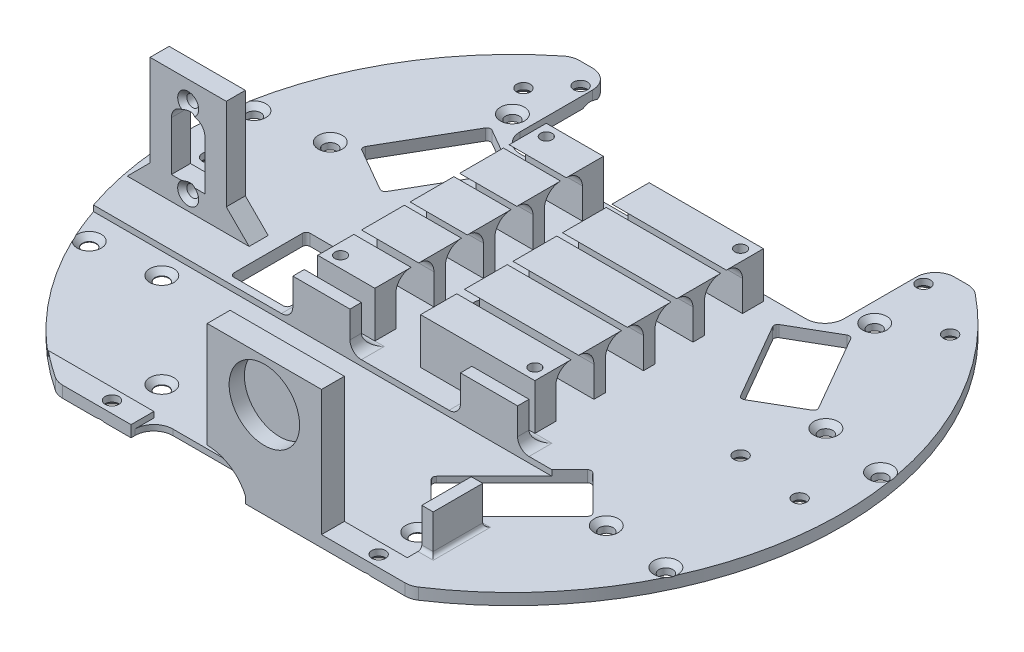
SolidWorks part; units mm, degrees
other "Camera1"
material "PET"
ref_plane "Front Plane" through (0, 0, 0) normal (0, 0, 1) x (1, 0, 0)
ref_plane "Top Plane" through (0, 0, 0) normal (0, 1, 0) x (1, 0, 0)
ref_plane "Right Plane" through (0, 0, 0) normal (1, 0, 0) x (0, 0, -1)
sketch "Sketch1" plane through (0, 0, 0) normal (0, 1, 0) x (1, 0, 0)
  line L0 (-52.6579, 68.6251) -> (52.6579, 68.6251)
  line L1 (52.6579, 68.6251) -> (0, 0) construction
  line L2 (0, 0) -> (-52.6579, 68.6251) construction
  line L3 (0, -100.6233) -> (0, 107.1722) construction
  line L4 (110.1779, 0) -> (-109.5879, 0) construction
  line L5 (0, 0) -> (40.7032, 23.5) construction
  line L6 (34.4532, 34.3253) -> (46.9532, 12.6747)
  line L7 (46.9532, 12.6747) -> (59.9436, 20.1747)
  line L8 (59.9436, 20.1747) -> (47.4436, 41.8253)
  line L9 (47.4436, 41.8253) -> (34.4532, 34.3253)
  line L10 (0, 0) -> (33.234, -33.234) construction
  line L11 (43.8406, -22.6274) -> (22.6274, -43.8406)
  line L12 (22.6274, -43.8406) -> (33.234, -54.4472)
  line L13 (33.234, -54.4472) -> (54.4472, -33.234)
  line L14 (54.4472, -33.234) -> (43.8406, -22.6274)
  line L15 (0, 0) -> (-33.234, -33.234) construction
  line L16 (-22.6274, -43.8406) -> (-33.234, -54.4472) construction
  line L17 (-33.234, -54.4472) -> (-54.4472, -33.234) construction
  line L18 (-54.4472, -33.234) -> (-43.8406, -22.6274) construction
  line L19 (-43.8406, -22.6274) -> (-22.6274, -43.8406) construction
  line L20 (-47.4436, 41.8253) -> (-34.4532, 34.3253)
  line L21 (-59.9436, 20.1747) -> (-47.4436, 41.8253)
  line L22 (-46.9532, 12.6747) -> (-59.9436, 20.1747)
  line L23 (-34.4532, 34.3253) -> (-46.9532, 12.6747)
  line L24 (0, 0) -> (-40.7032, 23.5) construction
  arc A0 (-52.6579, 68.6251) -> (52.6579, 68.6251) centre (0, 0) ccw
  arc A1 (52.6579, 68.6251) -> (-52.6579, 68.6251) centre (0, 0) ccw construction
  point P11 (40.7032, 23.5)
  point P18 (33.234, -33.234)
  dimension "D1" = 173
  dimension "D2" = 75
  dimension "D3" = 60
  dimension "D4" = 45
  dimension "D5" = 62
  dimension "D6" = 15
  dimension "D7" = 25
  dimension "D8" = 30
extrude "Boss-Extrude1" add sketch "Sketch1" along normal blind 3
hole_wizard "CSK for M3 Countersunk Flat Head Screw8" positions "Sketch42" profile "Sketch43" countersink size "M3" standard "DIN" end condition through all
sketch "Sketch42" plane through (0, 3, 0) normal (0, 1, 0) x (1, 0, 0)
  line L0 (0, 0) -> (56.2917, 32.5) construction
  line L2 (0, 0) -> (45.9619, -45.9619) construction
  line L4 (0, -101.1131) -> (0, 85.3109) construction
  line L6 (100.6982, 0) -> (-96.3433, 0) construction
  line L9 (58.3363, -33.5876) -> (33.5876, -58.3363) construction
  line L11 (65.0417, 17.3446) -> (47.5417, 47.6554) construction
  line L12 (0, 0) -> (-56.2917, 32.5) construction
  line L13 (-65.0417, 17.3446) -> (-47.5417, 47.6554) construction
  line L14 (-58.3363, -33.5876) -> (-33.5876, -58.3363) construction
  line L15 (0, 0) -> (-45.9619, -45.9619) construction
  line L16 (0, 0) -> (-75.6767, -35.2886) construction
  line L18 (-82.2314, 14.4996) -> (0, 0) construction
  arc A4 (-75.6767, -35.2886) -> (-82.2314, 14.4996) centre (0, 0) cw construction
  point P20 (58.3363, -33.5876)
  point P21 (33.5876, -58.3363)
  point P24 (65.0417, 17.3446)
  point P25 (47.5417, 47.6554)
  point P28 (56.2917, 32.5)
  point P29 (45.9619, -45.9619)
  point P42 (-47.5417, 47.6554)
  point P43 (-65.0417, 17.3446)
  point P44 (-33.5876, -58.3363)
  point P45 (-58.3363, -33.5876)
  point P51 (-75.6767, -35.2886)
  point P85 (-82.2314, 14.4996)
  point P103 (75.6767, -35.2886)
  point P104 (82.2314, 14.4996)
  dimension "D6" = 25
  dimension "D4" = 83.5
  dimension "D1" = 45
  dimension "D2" = 60
  dimension "D3" = 35
  dimension "D5" = 65
  dimension "5" = 35
sketch "Sketch43" plane through (82.2314, 3, -14.4996) normal (1, 0, 0) x (0, 0, 1)
  line L0 (0, 0) -> (0, 3)
  line L1 (0, 3) -> (1.8, 3)
  line L2 (1.8, 3) -> (1.8, 1.35)
  line L3 (1.8, 1.35) -> (3.15, 0)
  line L5 (3.15, 0) -> (0, 0)
  line L6 (-1.8, 1.35) -> (-3.15, 0) construction
  line L11 (0, -6.35) -> (0, 107.95) construction
  dimension "Thru Hole Dia." = 3.6
  dimension "Thru Hole Depth" = 3
  dimension "Near C'Sink Dia." = 6.3
  dimension "Near C'Sink Angle" = 90
hole_wizard "CSK for M3 Countersunk Flat Head Screw9" positions "Sketch46" profile "Sketch47" countersink size "M3" standard "DIN" end condition through all
sketch "Sketch46" plane through (0, 0, 0) normal (0, -1, 0) x (-1, 0, 0)
  point P0 (-60, 55)
  point P2 (-60, 0)
  point P4 (52, 55)
  point P14 (8, 0)
  point P19 (-45, 63)
  point P21 (45, 63)
  point P32 (-77.5, -2)
  point P34 (77.5, -2)
  point P36 (35, -70)
  point P38 (-35, -70)
  dimension "D2" = 60
  dimension "D3" = 112
  dimension "D4" = 55
  dimension "D5" = 68
  dimension "D1" = 55
  dimension "D7" = 45
  dimension "D6" = 90
  dimension "D8" = 63
  dimension "D9" = 2
  dimension "D10" = 155
  dimension "D11" = 77.5
  dimension "D12" = 35
  dimension "D13" = 70
  dimension "D14" = 70
sketch "Sketch47" plane through (60, 0, -55) normal (1, 0, 0) x (0, 0, -1)
  line L0 (0, 0) -> (0, 3)
  line L1 (0, 3) -> (1.8, 3)
  line L2 (1.8, 3) -> (1.8, 1.35)
  line L3 (1.8, 1.35) -> (3.15, 0)
  line L5 (3.15, 0) -> (0, 0)
  line L6 (-1.8, 1.35) -> (-3.15, 0) construction
  line L11 (0, -6.35) -> (0, 107.95) construction
  dimension "Thru Hole Dia." = 3.6
  dimension "Thru Hole Depth" = 3
  dimension "Near C'Sink Dia." = 6.3
  dimension "Near C'Sink Angle" = 90
sketch "Sketch39" plane through (0, 3, 0) normal (0, 1, 0) x (1, 0, 0)
  line L0 (-39.5, -28) -> (-81.8428, -28)
  line L1 (39.5, -67) -> (39.5, -28)
  line L2 (39.5, -28) -> (-39.5, -28)
  line L3 (-39.5, -28) -> (-39.5, -67) construction
  line L4 (-39.5, -67) -> (39.5, -67)
  line L5 (-39.5, -67) -> (-54.7106, -67)
  arc A0 (-52.6579, 68.6251) -> (-85.0107, 15.9823) centre (0, 0) ccw construction
  arc A1 (-81.8428, -28) -> (-54.7106, -67) centre (0, 0) ccw
  point P5 (0, -28)
  dimension "D1" = 39
  dimension "D2" = 79
  dimension "D3" = 28
extrude "Cut-Extrude7" cut sketch "Sketch39" against normal blind 1.5
sketch "Sketch45" plane through (0, 3, 0) normal (0, 1, 0) x (1, 0, 0)
  line L0 (52.6579, 68.6251) -> (-52.6579, 68.6251) construction
  line L1 (42.5, 68.6251) -> (-42.5, 68.6251)
  line L2 (42.5, 68.6251) -> (42.5, 39.6251)
  line L3 (42.5, 39.6251) -> (-42.5, 39.6251)
  line L4 (-42.5, 68.6251) -> (-42.5, 39.6251)
  point P6 (0, 68.6251)
  dimension "D1" = 85
  dimension "D2" = 29
extrude "Cut-Extrude8" cut sketch "Sketch45" against normal through all
sketch "Sketch48" plane through (0, 3, 0) normal (0, 1, 0) x (1, 0, 0)
  line L38 (38.468, -28) -> (-81.8428, -28) construction
  line L39 (-29.532, -28) -> (-14.532, -28)
  line L40 (-29.532, -28) -> (-29.532, -25)
  line L41 (-29.532, -25) -> (-14.532, -25)
  line L42 (-14.532, -28) -> (-14.532, -25)
  line L43 (38.468, -28) -> (-81.8428, -28) construction
  line L44 (29.468, -28) -> (14.468, -28)
  line L45 (29.468, -28) -> (29.468, -25)
  line L46 (29.468, -25) -> (14.468, -25)
  line L47 (14.468, -28) -> (14.468, -25)
  line L52 (39.5, -67) -> (39.5, -48.1812) construction
  line L57 (39.5, -50.1812) -> (42.5, -50.1812)
  line L58 (39.5, -50.1812) -> (39.5, -63.1812)
  line L59 (39.5, -63.1812) -> (42.5, -63.1812)
  line L60 (42.5, -50.1812) -> (42.5, -63.1812)
  dimension "D1" = 3
  dimension "D2" = 15
  dimension "D3" = 29
  dimension "D4" = 9
  dimension "D5" = 2
  dimension "D6" = 13
extrude "Boss-Extrude4" add sketch "Sketch48" along normal blind 10
fillet "Fillet11" radius 3 6 edges at (-29.532, 3, 26.5) (-22.032, 3, 25) (-14.532, 3, 26.5) (14.468, 3, 26.5) (21.968, 3, 25) (29.468, 3, 26.5)
hole_wizard "CSK for M3 Countersunk Flat Head Screw10" positions "Sketch50" profile "Sketch51" countersink size "M3" standard "DIN" end condition up to next
sketch "Sketch50" plane through (0, 1.5, 0) normal (0, 1, 0) x (1, 0, 0)
  point P6 (-58.3363, -33.5876)
  point P9 (-75.6767, -35.2886)
  point P18 (-33.5876, -58.3363)
  point P21 (33.5876, -58.3363)
sketch "Sketch51" plane through (-58.3363, 1.5, 33.5876) normal (1, 0, 0) x (0, 0, 1)
  line L0 (0, 0) -> (0, 1.5)
  line L1 (0, 1.5) -> (1.8, 1.5)
  line L2 (1.8, 1.5) -> (1.8, 1.35)
  line L3 (1.8, 1.35) -> (3.15, 0)
  line L5 (3.15, 0) -> (0, 0)
  line L6 (-1.8, 1.35) -> (-3.15, 0) construction
  line L11 (0, -6.35) -> (0, 107.95) construction
  dimension "Thru Hole Dia." = 3.6
  dimension "Thru Hole Depth" = 1.5
  dimension "Near C'Sink Dia." = 6.3
  dimension "Near C'Sink Angle" = 90
fillet "Fillet14" radius 1 3 edges at (42.5, 3, 56.6812) (41, 3, 63.1812) (41, 3, 50.1812)
sketch "Sketch52" plane through (0, 3, 0) normal (0, 1, 0) x (1, 0, 0)
  line L1 (-78, -12) -> (-58, -12)
  line L2 (-78, -12) -> (-78, -17)
  line L3 (-78, -17) -> (-58, -17)
  line L4 (-58, -12) -> (-58, -17)
  point P4 (-68, -12)
  point P6 (-68, -17)
  dimension "D1" = 68
  dimension "D2" = 12
  dimension "D3" = 5
  dimension "D4" = 20
extrude "Boss-Extrude5" add sketch "Sketch52" along normal blind 30
sketch "Sketch53" plane through (0, 0, 17) normal (0, 0, 1) x (1, 0, 0)
  line L5 (-78, 33) -> (-58, 33) construction
  line L8 (-78, 3) -> (-58, 3) construction
  line L16 (-72.4, 9.15) -> (-72.4, 22.1)
  line L18 (-63.6, 22.1) -> (-63.6, 9.15)
  line L19 (-63.6, 9.15) -> (-72.4, 9.15)
  line L20 (-68, 25.35) -> (-68, 9.15) construction
  line L21 (-66.85, 25.35) -> (-69.15, 25.35)
  arc A5 (-72.4, 22.1) -> (-69.15, 25.35) centre (-69.15, 22.1) cw
  arc A7 (-63.6, 22.1) -> (-66.85, 25.35) centre (-66.85, 22.1) ccw
  point P1 (-68, 17.25)
  point P37 (-68, 25.35)
  point P38 (-68, 33)
  dimension "D8" = 3.25
  dimension "D7" = 8.8
  dimension "D9" = 16.2
  dimension "D1" = 14.25
hole_wizard "CSK for M2.5 Countersunk Flat Head Screw1" positions "Sketch54" profile "Sketch55" countersink size "M2.5" standard "DIN" end condition up to next
sketch "Sketch54" plane through (0, 0, 17) normal (0, 0, 1) x (1, 0, 0)
  line L0 (-68, 7) -> (-68, 27.5) construction
  line L2 (-78, 3) -> (-58, 3) construction
  point P0 (-68, 7)
  point P2 (-68, 27.5)
  point P12 (-68, 3)
  point P13 (-68, 17.25)
  dimension "D1" = 20.5
  dimension "D2" = 4
sketch "Sketch55" plane through (-68, 7, 17) normal (1, 0, 0) x (0, -1, 0)
  line L0 (0, 0) -> (0, 5)
  line L1 (0, 5) -> (1.55, 5)
  line L2 (1.55, 5) -> (1.55, 1.2)
  line L3 (1.55, 1.2) -> (2.75, 0)
  line L5 (2.75, 0) -> (0, 0)
  line L6 (-1.55, 1.2) -> (-2.75, 0) construction
  line L11 (0, -6.35) -> (0, 107.95) construction
  dimension "Thru Hole Dia." = 3.1
  dimension "Thru Hole Depth" = 5
  dimension "Near C'Sink Dia." = 5.5
  dimension "Near C'Sink Angle" = 90
extrude "Cut-Extrude9" cut sketch "Sketch53" against normal up to next
chamfer "Chamfer1" distance 6 angle 45 2 edges at (-58, 3, 14.5) (-78, 3, 14.5)
sketch "Sketch56" plane through (0, 3, 0) normal (0, 1, 0) x (1, 0, 0)
  line L0 (-54.7106, -67) -> (39.5, -67) construction
  line L1 (-7, -67) -> (23, -67)
  line L2 (-7, -67) -> (-7, -73)
  line L3 (-7, -73) -> (23, -73)
  line L4 (23, -67) -> (23, -73)
  point P8 (8, -67)
  dimension "D1" = 6
  dimension "D2" = 30
  dimension "D3" = 31.5
extrude "Boss-Extrude6" add sketch "Sketch56" along normal blind 33
sketch "Sketch57" plane through (0, 0, 73) normal (0, 0, 1) x (1, 0, 0)
  line L0 (-7, 3) -> (23, 3) construction
  line L1 (-7, 36) -> (23, 36) construction
  circle A0 centre (8, 25) radius 9.25
  point P6 (8, 36)
  dimension "D1" = 18.5
  dimension "D2" = 22
extrude "Cut-Extrude10" cut sketch "Sketch57" against normal blind 4
sketch "Sketch58" plane through (0, 3, 0) normal (0, 1, 0) x (1, 0, 0)
  line L0 (-46.4031, -73) -> (-27, -73)
  line L1 (-27, -73) -> (-27, -67)
  line L2 (-54.7106, -67) -> (-7, -67) construction
  line L3 (-27, -67) -> (-7, -67)
  line L4 (-7, -67) -> (-7, -73) construction
  line L5 (-7, -67) -> (-7, -73)
  line L6 (-7, -73) -> (46.4031, -73)
  arc A1 (-52.6579, 68.6251) -> (-85.0107, 15.9823) centre (0, 0) ccw construction
  arc A2 (-46.4031, -73) -> (46.4031, -73) centre (0, 0) ccw
  dimension "D1" = 20
extrude "Cut-Extrude11" cut sketch "Sketch58" against normal blind 4
sketch "Sketch60" plane through (0, 0, 73) normal (0, 0, 1) x (1, 0, 0)
  line L1 (-7, 0) -> (3, 0)
  line L2 (-7, 0) -> (-7, 1.9)
  line L3 (-7, 1.9) -> (3, 1.9)
  line L4 (3, 0) -> (3, 1.9)
  dimension "D1" = 10
  dimension "D2" = 1.9
extrude "Cut-Extrude14" cut sketch "Sketch60" against normal blind 6
fillet "Fillet13" radius 5 11 edges at (-42.5, 0.554, -63.6995) (-42.5, 1.5, -39.6251) (42.5, 1.5, -68.6251) (42.5, 1.5, -39.6251) (-42.5, 1.5, -68.6251) (-52.6579, 1.5, -68.6251) (52.6579, 1.5, -68.6251) (46.4031, 1.5, 73) (-46.4031, 1.5, 73) (-27, 0.75, 67) (3, 0.75, 67)
sketch "Sketch61" plane through (0, 3, 0) normal (0, 1, 0) x (1, 0, 0)
  line L25 (28, 38) -> (-2, 38)
  line L26 (28, 38) -> (28, -22)
  line L27 (28, -22) -> (-2, -22)
  line L28 (-2, 38) -> (-2, -22)
  line L30 (-14, 38) -> (-29, 38)
  line L31 (-14, 38) -> (-14, -22)
  line L32 (-14, -22) -> (-29, -22)
  line L33 (-29, 38) -> (-29, -22)
  line L34 (11.468, -22) -> (32.468, -22) construction
  circle A0 centre (-8, 0) radius 1.8 construction
  dimension "D1" = 60
  dimension "D2" = 30
  dimension "D3" = 6
  dimension "D4" = 15
  dimension "D5" = 6
  dimension "D6" = 0
extrude "Boss-Extrude7" add sketch "Sketch61" along normal blind 12
sketch "Sketch62" plane through (28, 0, 0) normal (1, 0, 0) x (0, 0, -1)
  line L0 (-16.5, 3) -> (-16.5, 11)
  line L1 (-22, 3) -> (38, 3) construction
  line L2 (-22, 15) -> (38, 15) construction
  line L3 (-6.5, 11) -> (-6.5, 3)
  line L4 (-6.5, 3) -> (-16.5, 3)
  line L5 (13.75, 15) -> (15.25, 15)
  line L6 (-3.5, 11) -> (-3.5, 3)
  line L7 (-3.5, 3) -> (6.5, 3)
  line L8 (6.5, 3) -> (6.5, 11)
  line L9 (9.5, 11) -> (9.5, 3)
  line L10 (9.5, 3) -> (19.5, 3)
  line L11 (19.5, 3) -> (19.5, 11)
  line L12 (-12.5, 15) -> (-10.5, 15)
  line L13 (-22, 15) -> (-22, 3) construction
  line L15 (0.75, 15) -> (2.25, 15)
  line L23 (22.5, 3) -> (32.5, 3)
  line L24 (22.5, 3) -> (22.5, 11)
  line L25 (26.75, 15) -> (28.25, 15)
  line L26 (32.5, 11) -> (32.5, 3)
  arc A0 (-16.5, 11) -> (-12.5, 15) centre (-12.5, 11) cw
  arc A1 (-10.5, 15) -> (-6.5, 11) centre (-10.5, 11) cw
  arc A2 (0.75, 15) -> (-3.5, 11) centre (0.75, 10.7422) ccw
  arc A3 (2.25, 15) -> (6.5, 11) centre (2.25, 10.7422) cw
  arc A4 (13.75, 15) -> (9.5, 11) centre (13.75, 10.7422) ccw
  arc A5 (15.25, 15) -> (19.5, 11) centre (15.25, 10.7422) cw
  arc A6 (22.5, 11) -> (26.75, 15) centre (26.75, 10.7422) cw
  arc A7 (28.25, 15) -> (32.5, 11) centre (28.25, 10.7422) cw
  point P34 (1.5, 15)
  point P36 (1.5, 3)
  point P39 (27.5, 15)
  point P40 (27.5, 3)
  point P55 (14.5, 15)
  point P56 (14.5, 3)
  dimension "D1" = 5.5
  dimension "D2" = 3
  dimension "D3" = 10
  dimension "D4" = 10
  dimension "D5" = 10
  dimension "D6" = 3
  dimension "D7" = 2
  dimension "D8" = 1.5
  dimension "D9" = 1.5
  dimension "D10" = 10
  dimension "D11" = 3
  dimension "D12" = 1.5
extrude "Cut-Extrude15" cut sketch "Sketch62" against normal up to surface (57 mm away) up to face at (-29, 9, -8)
hole_wizard "Tap Drill for M3 Tap1" positions "Sketch63" profile "Sketch64" hole size "M3" standard "ISO" end condition through all
sketch "Sketch63" plane through (0, 15, 0) normal (0, 1, 0) x (1, 0, 0)
  line L0 (-2, -22) -> (28, -22) construction
  line L1 (28, -22) -> (28, -12.5) construction
  line L2 (28, 38) -> (-2, 38) construction
  line L3 (28, 15.25) -> (28, 26.75) construction
  line L4 (-29, -12.5) -> (-29, -22) construction
  point P0 (-26, -19)
  point P2 (-26, 35)
  point P4 (25, 35)
  point P6 (25, -19)
  dimension "D1" = 3
  dimension "D2" = 3
  dimension "D3" = 3
  dimension "D4" = 3
  dimension "D5" = 3
sketch "Sketch64" plane through (-26, 15, 19) normal (1, 0, 0) x (0, 0, 1)
  line L0 (0, 0) -> (0, 15.2183)
  line L1 (0, 15.2183) -> (1.25, 15.2183)
  line L2 (1.25, 15.2183) -> (1.25, 0)
  line L5 (1.25, 0) -> (0, 0)
  line L11 (0, -6.35) -> (0, 107.95) construction
  dimension "Thru Hole Dia." = 2.5
  dimension "Thru Hole Depth" = 15.2183
sketch "Sketch65" plane through (0, 0, 73) normal (0, 0, 1) x (1, 0, 0)
  line L0 (-7, 36) -> (-7, 1.9) construction
  line L1 (-7, 8.3174) -> (-7, 1.9)
  line L2 (3, 1.9) -> (-7, 1.9) construction
  line L3 (-7, 1.9) -> (3, 1.9)
  arc A0 (3, 1.9) -> (-7, 8.3174) centre (-7, -2.6826) ccw
  dimension "D1" = 11
extrude "Cut-Extrude16" cut sketch "Sketch65" against normal up to next
sketch "Sketch66" plane through (0, 3, 0) normal (0, 1, 0) x (1, 0, 0)
  line L0 (-32.532, -28) -> (-81.8428, -28) construction
  line L1 (-47, -6) -> (-34, -6)
  line L2 (-48, -7) -> (-48, -25)
  line L3 (-47, -26) -> (-34, -26)
  line L4 (-33, -7) -> (-33, -25)
  line L5 (-52, -12) -> (-52, -17) construction
  arc A0 (-34, -6) -> (-33, -7) centre (-34, -7) cw
  arc A1 (-34, -26) -> (-33, -25) centre (-34, -25) ccw
  arc A2 (-48, -25) -> (-47, -26) centre (-47, -25) ccw
  arc A3 (-47, -6) -> (-48, -7) centre (-47, -7) ccw
  point P10 (-33, -6)
  point P17 (-48, -6)
  dimension "D5" = 1
  dimension "D1" = 22
  dimension "D2" = 4
  dimension "D3" = 15
  dimension "D4" = 20
extrude "Cut-Extrude17" cut sketch "Sketch66" against normal through all
fillet "Fillet15" radius 1 12 edges at (47.4436, 1.5, -41.8253) (34.4532, 1.5, -34.3253) (46.9532, 1.5, -12.6747) (59.9436, 1.5, -20.1747) (22.6274, 0.75, 43.8406) (43.8406, 1.5, 22.6274) (54.4472, 1.5, 33.234) (33.234, 0.75, 54.4472) (-46.9532, 1.5, -12.6747) (-59.9436, 1.5, -20.1747) (-47.4436, 1.5, -41.8253) (-34.4532, 1.5, -34.3253)
sketch "Sketch67" plane through (0, 15, 0) normal (0, 1, 0) x (1, 0, 0)
  circle A0 centre (-26, -19) radius 1.5
  circle A1 centre (25, -19) radius 1.5
  circle A2 centre (25, 35) radius 1.5
  circle A3 centre (-26, 35) radius 1.5
  dimension "D1" = 3
extrude "Cut-Extrude18" cut sketch "Sketch67" against normal through all
equation "\"D7@Sketch46\"=\"D6@Sketch46\"/2"
equation "\"D11@Sketch46\"=\"D10@Sketch46\"/2"
equation "\"D12@Sketch46\"=\"D13@Sketch46\"/2"
equation "\"D2@Sketch46\"=\"D3@Sketch46\"/2+4"
equation "\"D7@Sketch53\"=8.2+0.6"
equation "\"D9@Sketch53\"=15.600000mm+0.6"
equation "\"D4@Sketch66\"=\"D1@Sketch66\"-2"
